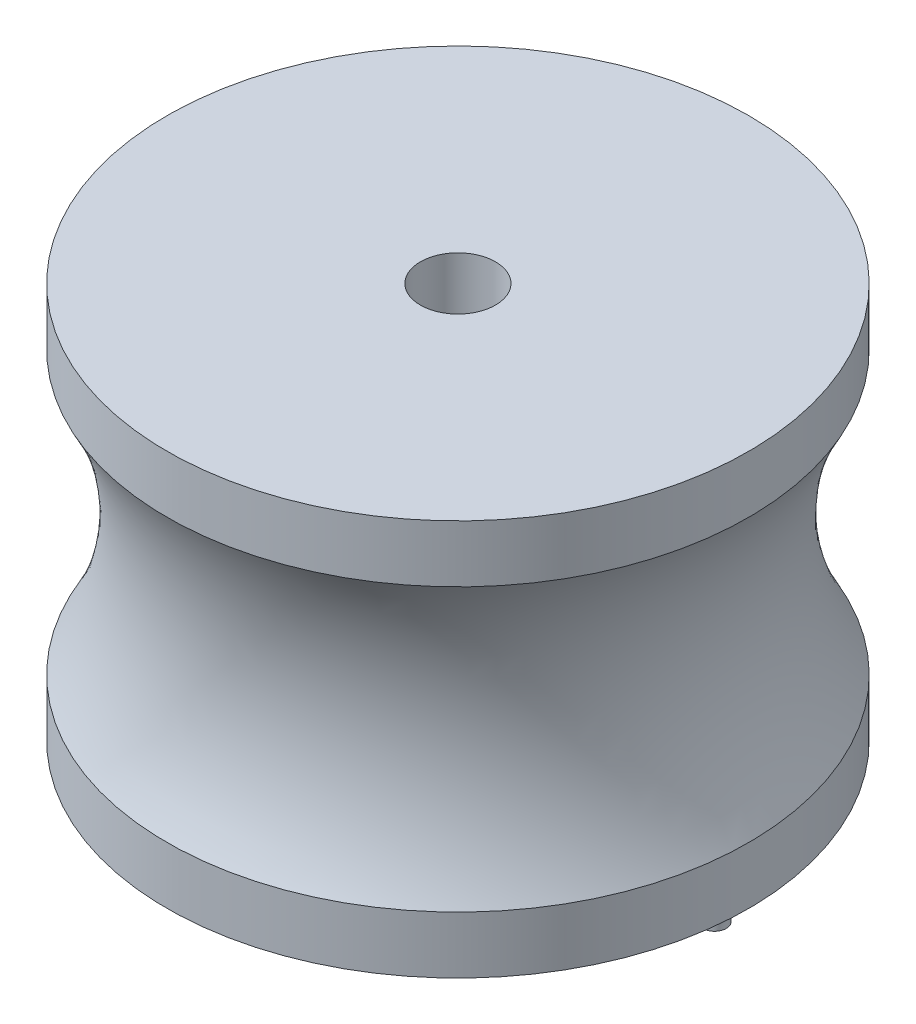
SolidWorks part; units mm, degrees
ref_plane "Front" through (0, 0, 0) normal (0, 0, 1) x (1, 0, 0)
ref_plane "Top" through (0, 0, 0) normal (0, 1, 0) x (1, 0, 0)
ref_plane "Right" through (0, 0, 0) normal (1, 0, 0) x (0, 0, -1)
sketch "Sketch2" plane through (0, 0, 0) normal (0, 1, 0) x (1, 0, 0)
  circle A0 centre (0, 0) radius 18.0975
  dimension "D1" = 36.195
extrude "Boss-Extrude1" add sketch "Sketch2" along normal blind 24.638
sketch "Sketch3" plane through (0, 24.638, 0) normal (0, 1, 0) x (1, 0, 0)
  circle A0 centre (0, 0) radius 2.3368
  dimension "D1" = 4.6736
extrude "Cut-Extrude1" cut sketch "Sketch3" against normal through all
sketch "Sketch4" plane through (0, 0, 0) normal (0, -1, 0) x (1, 0, 0)
  circle A0 centre (15.973, 0) radius 0.7239
  circle A1 centre (-16.8472, 0) radius 0.7239
  dimension "D1" = 1.4478
  dimension "D2" = 1.4478
extrude "Boss-Extrude2" add sketch "Sketch4" along normal blind 1.778
sketch "Sketch7" plane through (0, 0, 0) normal (0, 0, 1) x (1, 0, 0)
  line L0 (-18.0975, 24.638) -> (-18.0975, 0) construction
  line L1 (18.0975, 24.638) -> (-18.0975, 24.638) construction
  line L2 (-18.0975, 0) -> (18.0975, 0) construction
  line L3 (-18.0975, 21.082) -> (-18.0975, 3.556)
  line L4 (-18.0975, 12.319) -> (-15.748, 12.319) construction
  arc A0 (-18.0975, 21.082) -> (-18.0975, 3.556) centre (-33.2646, 12.319) cw
  dimension "D3" = 2.3495
  dimension "D1" = 3.556
  dimension "D2" = 3.556
sketch "Sketch8" plane through (0, 0, 0) normal (0, 0, 1) x (1, 0, 0)
  line L0 (0, 24.7357) -> (0, 0) construction
revolve "Cut-Revolve1" cut sketch "Sketch7" angle 360 about L0
